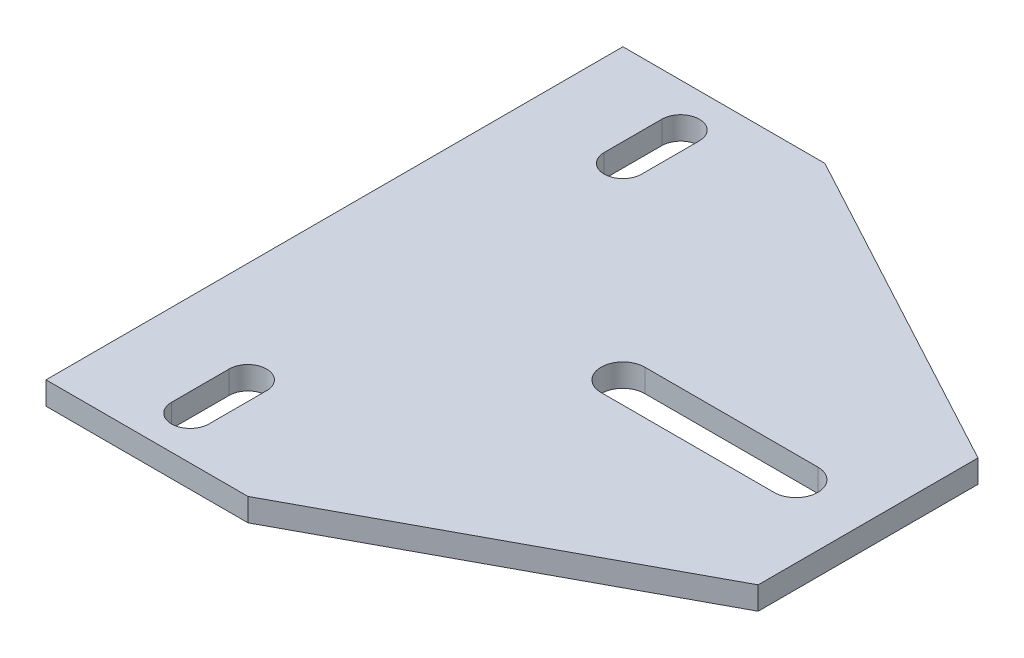
SolidWorks part; units mm, degrees
material "Fundición maleable"
ref_plane "Alzado" through (0, 0, 0) normal (0, 0, 1) x (1, 0, 0)
ref_plane "Planta" through (0, 0, 0) normal (0, 1, 0) x (1, 0, 0)
ref_plane "Vista lateral" through (0, 0, 0) normal (1, 0, 0) x (0, 0, -1)
sketch "Croquis1" plane through (0, 0, 0) normal (0, 1, 0) x (1, 0, 0)
  line L0 (0, -100) -> (0, 100)
  line L1 (0, 100) -> (70, 100)
  line L2 (70, 100) -> (185, 38.1)
  line L3 (185, 38.1) -> (185, -38.1)
  line L4 (185, -38.1) -> (70, -100)
  line L5 (70, -100) -> (0, -100)
  line L6 (0, 0) -> (185, 0) construction
  line L7 (70, 100) -> (70, -100) construction
  line L8 (100, 0) -> (160, 0) construction
  line L9 (100, 7.5979) -> (160, 7.5979)
  line L10 (100, -7.5979) -> (160, -7.5979)
  line L11 (35, -85) -> (35, -65) construction
  line L12 (28.5, -85) -> (28.5, -65)
  line L13 (41.5, -85) -> (41.5, -65)
  line L14 (35, 85) -> (35, 65) construction
  line L15 (28.5, 85) -> (28.5, 65)
  line L16 (41.5, 85) -> (41.5, 65)
  circle A0 centre (160, 0) radius 6.35
  circle A1 centre (100, 0) radius 6.35
  arc A2 (100, 7.5979) -> (100, -7.5979) centre (100, 0) ccw
  arc A3 (160, -7.5979) -> (160, 7.5979) centre (160, 0) ccw
  arc A4 (28.5, -85) -> (41.5, -85) centre (35, -85) ccw
  arc A5 (41.5, -65) -> (28.5, -65) centre (35, -65) ccw
  arc A6 (28.5, 85) -> (41.5, 85) centre (35, 85) cw
  arc A7 (41.5, 65) -> (28.5, 65) centre (35, 65) cw
  point P0 (185, 0)
  point P4 (0, 0)
  point P15 (130, 0)
  point P20 (35, -75)
  point P29 (35, 75)
  dimension "D2" = 12.7
  dimension "D8" = 12.7
  dimension "D11" = 6.5
  dimension "D1" = 200
  dimension "D3" = 185
  dimension "D4" = 20
  dimension "D5" = 70
  dimension "D6" = 76.2
  dimension "D7" = 30
  dimension "D9" = 60
  dimension "D10" = 15
  dimension "D12" = 35
extrude "Saliente-Extruir1" add sketch "Croquis1" along normal blind 7.9375 contours L5 L4 L3 L2 L1 L0 A5 L13 A4 L12 A3 L10 A2 L9 L16 A7 L15 A6
